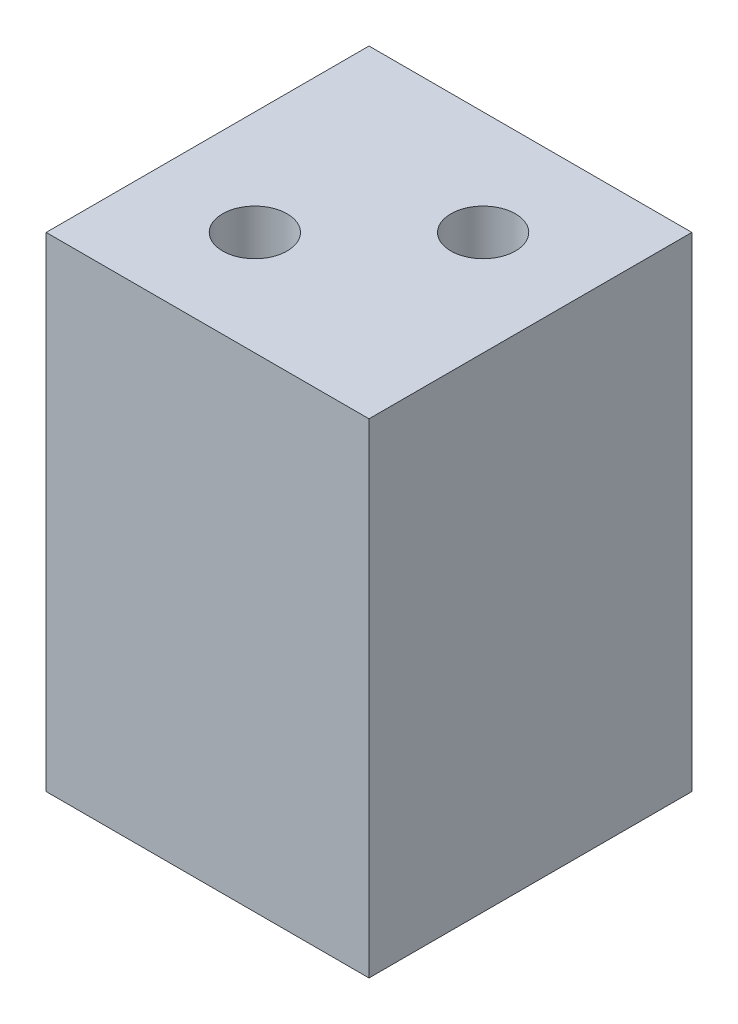
SolidWorks part; units mm, degrees
ref_plane "Front Plane" through (0, 0, 0) normal (0, 0, 1) x (1, 0, 0)
ref_plane "Top Plane" through (0, 0, 0) normal (0, 1, 0) x (1, 0, 0)
ref_plane "Right Plane" through (0, 0, 0) normal (1, 0, 0) x (0, 0, -1)
sketch "Sketch1" plane through (0, 0, 0) normal (0, 1, 0) x (1, 0, 0)
  line L0 (-15, -15) -> (15, 15) construction
  line L1 (-15, 15) -> (15, 15)
  line L2 (-15, 15) -> (-15, -15)
  line L3 (-15, -15) -> (15, -15)
  line L4 (15, 15) -> (15, -15)
  circle A0 centre (-5.3033, -5.3033) radius 3
  circle A1 centre (5.3033, 5.3033) radius 3
  point P4 (0, 0)
  dimension "D3" = 6
  dimension "D4" = 6
  dimension "D1" = 30
  dimension "D2" = 30
  dimension "D5" = 15
  dimension "D6" = 7.5
extrude "Boss-Extrude1" add sketch "Sketch1" along normal blind 45
